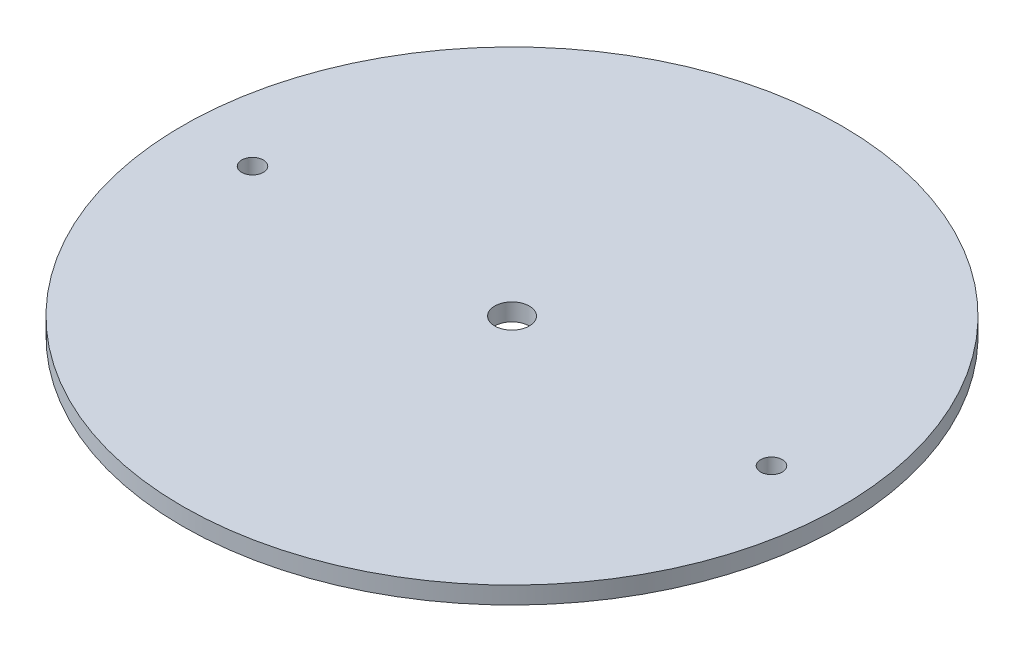
SolidWorks part; units mm, degrees
ref_plane "Front Plane" through (0, 0, 0) normal (0, 0, 1) x (1, 0, 0)
ref_plane "Top Plane" through (0, 0, 0) normal (0, 1, 0) x (1, 0, 0)
ref_plane "Right Plane" through (0, 0, 0) normal (1, 0, 0) x (0, 0, -1)
sketch "Sketch1" plane through (0, 0, 0) normal (0, 1, 0) x (1, 0, 0)
  line L0 (0, 0) -> (0, -39.219) construction
  line L1 (0, 0) -> (-60, 0) construction
  circle A0 centre (0, 0) radius 76.2
  circle A1 centre (0, 0) radius 4
  circle A2 centre (-60, 0) radius 2.5
  circle A3 centre (60, 0) radius 2.5
  dimension "D1" = 152.4
  dimension "D2" = 8
  dimension "D3" = 5
  dimension "D4" = 60
extrude "Boss-Extrude1" add sketch "Sketch1" along normal blind 4 contours A0 A1
